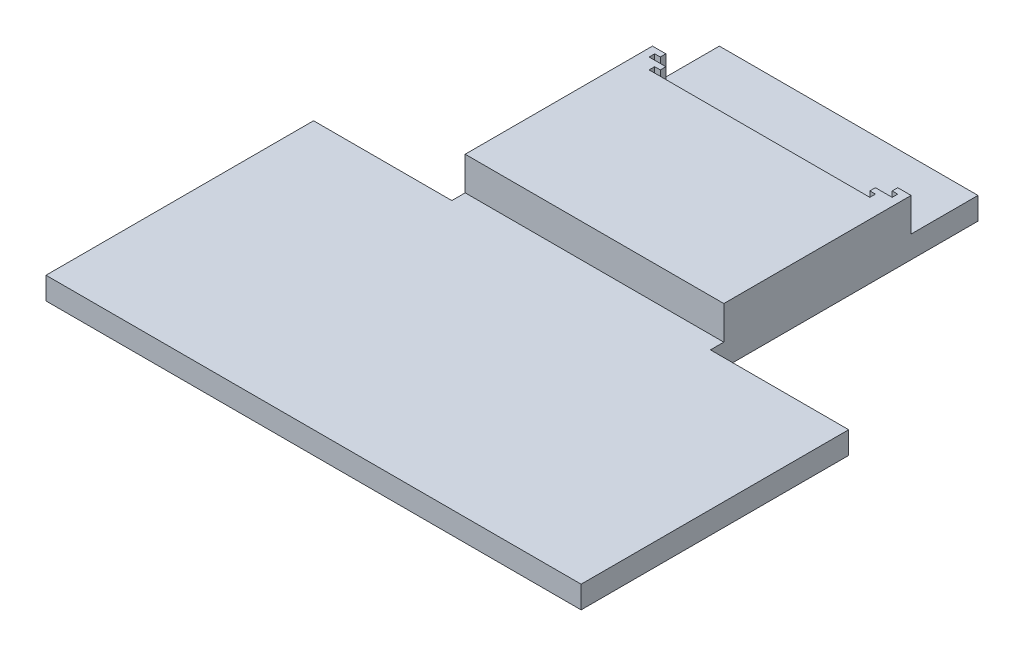
SolidWorks part; units mm, degrees
ref_plane "Alzado" through (0, 0, 0) normal (0, 0, 1) x (1, 0, 0)
ref_plane "Planta" through (0, 0, 0) normal (0, 1, 0) x (1, 0, 0)
ref_plane "Vista lateral" through (0, 0, 0) normal (1, 0, 0) x (0, 0, -1)
sketch "Base-Croquis" plane through (0, 0, 0) normal (0, 1, 0) x (1, 0, 0)
  line L1 (60, -60) -> (-60, -60)
  line L2 (60, -60) -> (60, 60)
  line L3 (60, 60) -> (-60, 60)
  line L4 (-60, -60) -> (-60, 60)
  line L5 (60, -60) -> (-60, 60) construction
  line L6 (60, 60) -> (-60, -60) construction
  point P0 (0, 0)
  dimension "D1" = 120
  dimension "D2" = 120
extrude "Base-Saliente" add sketch "Base-Croquis" along normal blind 5
sketch "Encaje-Ruedas-Croquis" plane through (0, 5, 0) normal (0, 1, 0) x (1, 0, 0)
  line L5 (-2.75, 0) -> (2.75, 0) construction
  line L6 (60, 60) -> (29, 60)
  line L7 (60, 60) -> (60, 0)
  line L8 (60, 0) -> (29, 0)
  line L9 (29, 60) -> (29, 0)
  line L10 (0, -2.75) -> (0, 2.75) construction
  line L11 (-60, 0) -> (-29, 0)
  line L12 (-29, 60) -> (-29, 0)
  line L13 (-60, 60) -> (-29, 60)
  line L14 (-60, 60) -> (-60, 0)
  line L15 (60, 60) -> (60, 65) construction
  line L16 (60, 65) -> (-60, 65) construction
  line L17 (-60, 65) -> (-60, 60) construction
  line L18 (-31, 65) -> (-31, 60) construction
  line L19 (31, 65) -> (31, 60) construction
  dimension "D1" = 31
  dimension "D2" = 60
  dimension "D3" = 5
  dimension "D4" = 29
  dimension "D5" = 29
extrude "Encaje-Ruedas-Cortar" cut sketch "Encaje-Ruedas-Croquis" against normal blind 5
sketch "Caja-Placas-Croquis-1" plane through (0, 5, 0) normal (0, 1, 0) x (1, 0, 0)
  line L0 (29, 40) -> (-29, 40) construction
  line L1 (29, 60) -> (29, 0) construction
  line L2 (-29, 0) -> (-29, 60) construction
  line L3 (29, 60) -> (-29, 60) construction
  line L4 (-29, 8) -> (29, 8) construction
  line L5 (0, 8) -> (0, 40) construction
  line L7 (21, 8) -> (-21, 8)
  line L8 (21, 8) -> (21, 40)
  line L9 (21, 40) -> (-21, 40)
  line L10 (-21, 8) -> (-21, 40)
  line L11 (21, 8) -> (-21, 40) construction
  line L12 (21, 40) -> (-21, 8) construction
  line L13 (-29, 45) -> (29, 45)
  line L14 (-29, 45) -> (-29, 3)
  line L15 (-29, 3) -> (29, 3)
  line L16 (29, 45) -> (29, 3)
  point P12 (0, 24)
  dimension "D1" = 20
  dimension "D2" = 32
  dimension "D3" = 42
  dimension "D4" = 42
  dimension "D5" = 5
extrude "Caja-Placas-Saliente-1" add sketch "Caja-Placas-Croquis-1" along normal blind 5
sketch "Caja-Placas-Croquis-2" plane through (0, 5, 0) normal (0, 1, 0) x (1, 0, 0)
  line L0 (0, 3) -> (0, 45) construction
  line L1 (-29, 3) -> (29, 3) construction
  line L2 (29, 45) -> (-29, 45) construction
  line L3 (29, 45) -> (-29, 45) construction
  line L4 (21, 8) -> (-21, 8)
  line L5 (21, 8) -> (21, 40)
  line L6 (21, 40) -> (-21, 40)
  line L7 (-21, 8) -> (-21, 40)
  line L8 (21, 8) -> (-21, 40) construction
  line L9 (21, 40) -> (-21, 8) construction
  point P6 (0, 24)
extrude "Caja-Placas-Cortar-2" cut sketch "Caja-Placas-Croquis-2" against normal blind 2.5
sketch "Caja-Placas-Croquis-3" plane through (0, 10, 0) normal (0, 1, 0) x (1, 0, 0)
  line L1 (-29, 45) -> (29, 45)
  line L2 (-29, 45) -> (-29, 3)
  line L3 (-29, 3) -> (29, 3)
  line L4 (29, 45) -> (29, 3)
extrude "Caja-Placas-Saliente-3" add sketch "Caja-Placas-Croquis-3" along normal blind 2.5
sketch "Caja-Placas-Croquis-4" plane through (0, 12.5, 0) normal (0, 1, 0) x (1, 0, 0)
  line L0 (-29, 40) -> (-29, 42.5) construction
  line L1 (-29, 42.5) -> (29, 42.5) construction
  line L2 (29, 45) -> (29, 3) construction
  line L3 (-29, 42.5) -> (-29, 45) construction
  line L4 (-29, 45) -> (29, 45) construction
  line L5 (29, 40) -> (-29, 40) construction
  line L6 (-29, 43.75) -> (29, 43.75) construction
  line L7 (-29, 41.25) -> (29, 41.25) construction
  line L8 (23.5, 42.5) -> (26, 42.5)
  line L9 (-23.5, 40) -> (23.5, 40)
  line L10 (-23.5, 41.25) -> (-23.5, 42.5)
  line L12 (23.5, 41.25) -> (23.5, 42.5)
  line L13 (-26, 45) -> (26, 45)
  line L14 (-26, 45) -> (-26, 43.75)
  line L15 (-26, 42.5) -> (-23.5, 42.5)
  line L16 (26, 45) -> (26, 43.75)
  line L17 (26, 43.75) -> (27.25, 43.75)
  line L19 (26, 42.5) -> (27.25, 42.5)
  line L20 (27.25, 43.75) -> (27.25, 42.5)
  line L21 (23.5, 41.25) -> (24.75, 41.25)
  line L23 (23.5, 40) -> (24.75, 40)
  line L24 (24.75, 41.25) -> (24.75, 40)
  line L25 (-23.5, 40) -> (-24.75, 40)
  line L27 (-23.5, 41.25) -> (-24.75, 41.25)
  line L28 (-24.75, 40) -> (-24.75, 41.25)
  line L29 (-26, 42.5) -> (-27.25, 42.5)
  line L31 (-26, 43.75) -> (-27.25, 43.75)
  line L32 (-27.25, 42.5) -> (-27.25, 43.75)
  dimension "D1" = 47
  dimension "D2" = 5.5
  dimension "D3" = 52
  dimension "D4" = 3
  dimension "D5" = 1.25
  dimension "D6" = 1.25
  dimension "D7" = 1.25
  dimension "D8" = 1.25
extrude "Caja-Placas-Cortar-4" cut sketch "Caja-Placas-Croquis-4" against normal blind 7.5
